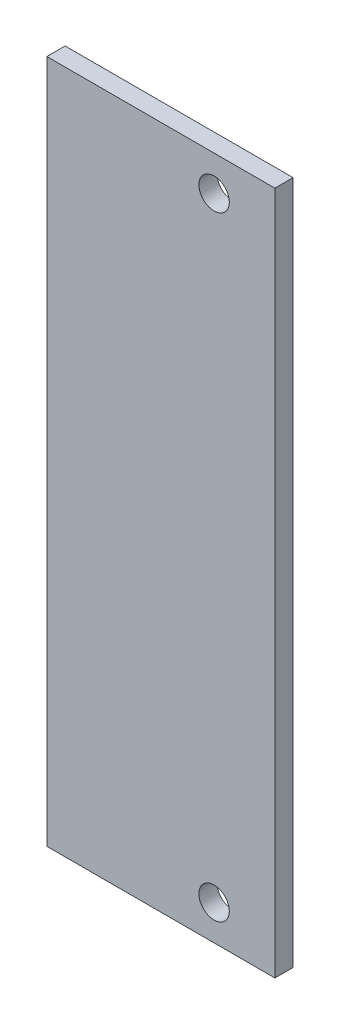
SolidWorks part; units mm, degrees
ref_plane "正面" through (0, 0, 0) normal (1, 0, 0) x (0, 1, 0)
ref_plane "平面" through (0, 0, 0) normal (0, 0, 1) x (0, 1, 0)
ref_plane "右側面" through (0, 0, 0) normal (0, 1, 0) x (-1, 0, 0)
sketch "ｽｹｯﾁ1" plane through (0, 0, 0) normal (0, 0, 1) x (0, 1, 0)
  line L0 (22.5, 8) -> (22.5, 0) construction
  line L1 (0, 0) -> (45, 0)
  line L2 (0, 0) -> (0, 8)
  line L3 (0, 8) -> (45, 8)
  line L4 (45, 0) -> (45, 8)
  line L5 (0, 6) -> (4.6, 6) construction
  line L6 (0, 6) -> (0, 2) construction
  line L7 (0, 2) -> (4.6, 2) construction
  line L8 (4.6, 6) -> (4.6, 2) construction
  line L10 (4.6, 4) -> (3.45, 5.9919) construction
  line L11 (3.45, 5.9919) -> (1.15, 5.9919) construction
  line L12 (1.15, 5.9919) -> (0, 4) construction
  line L13 (0, 4) -> (1.15, 2.0081) construction
  line L14 (1.15, 2.0081) -> (3.45, 2.0081) construction
  line L15 (3.45, 2.0081) -> (4.6, 4) construction
  circle A2 centre (2.3, 4) radius 1.9919 construction
  circle A3 centre (2.3, 4) radius 1
  circle A4 centre (42.7, 4) radius 1
  dimension "D6" = 4.6
  dimension "D7" = 2
  dimension "D1" = 8
  dimension "D2" = 45
  dimension "D3" = 4.6
  dimension "D4" = 4
  dimension "D5" = 2
extrude "ﾎﾞｽ - 押し出し1" add sketch "ｽｹｯﾁ1" against normal blind 1.2
sketch "ｽｹｯﾁ3" plane through (-8, 0, 0) normal (-1, 0, 0) x (0, -1, 0)
  line L1 (-45, 0) -> (0, 0)
  line L2 (-45, 0) -> (-45, -1.2)
  line L3 (-45, -1.2) -> (0, -1.2)
  line L4 (0, 0) -> (0, -1.2)
extrude "ﾎﾞｽ - 押し出し2" add sketch "ｽｹｯﾁ3" along normal blind 7
sketch "ｽｹｯﾁ4" plane through (0, 0, -1.2) normal (0, 0, -1) x (1, 0, 0)
  line L1 (0, 0) -> (-8, 0)
  line L2 (0, 0) -> (0, -4.6)
  line L3 (0, -4.6) -> (-8, -4.6)
  line L4 (-8, 0) -> (-8, -4.6)
  line L5 (0, -45) -> (-8, -45)
  line L6 (0, -45) -> (0, -40.4)
  line L7 (0, -40.4) -> (-8, -40.4)
  line L8 (-8, -45) -> (-8, -40.4)
  dimension "D1" = 8
  dimension "D2" = 4.6
  dimension "D3" = 4.6
  dimension "D4" = 8
